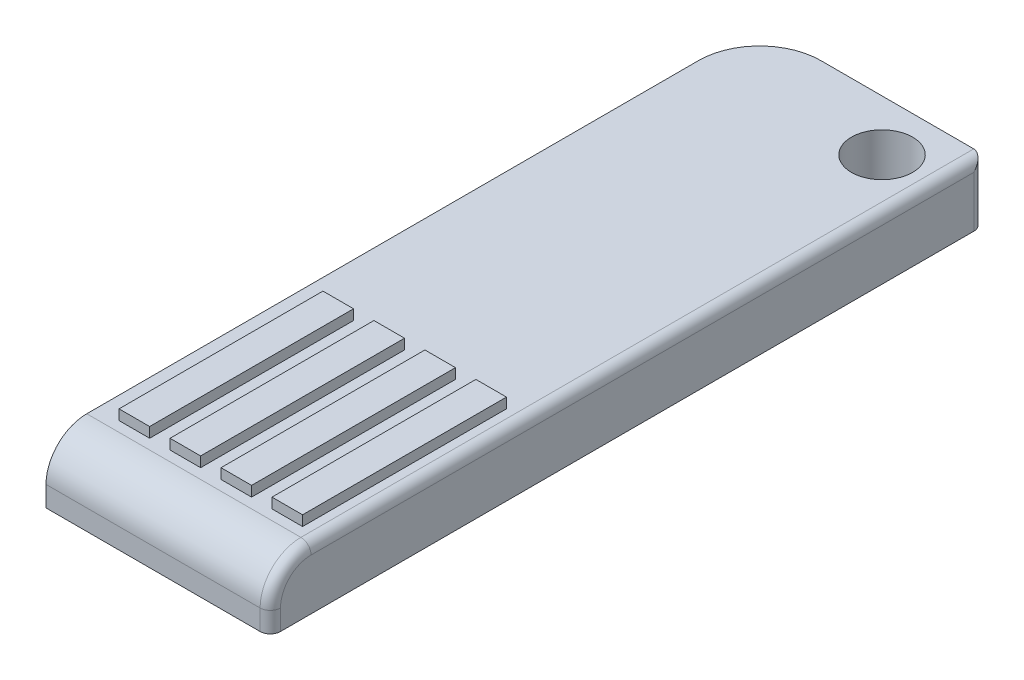
SolidWorks part; units mm, degrees
ref_plane "Front Plane" through (0, 0, 0) normal (0, 0, 1) x (1, 0, 0)
ref_plane "Top Plane" through (0, 0, 0) normal (0, 1, 0) x (1, 0, 0)
ref_plane "Right Plane" through (0, 0, 0) normal (1, 0, 0) x (0, 0, -1)
sketch "Sketch1" plane through (0, 0, 0) normal (0, 1, 0) x (1, 0, 0)
  line L1 (-5.5, 17.5) -> (5.5, 17.5)
  line L2 (-5.5, 17.5) -> (-5.5, -17.5)
  line L3 (-5.5, -17.5) -> (5.5, -17.5)
  line L4 (5.5, 17.5) -> (5.5, -17.5)
  line L5 (-5.5, 17.5) -> (5.5, -17.5) construction
  line L6 (-5.5, -17.5) -> (5.5, 17.5) construction
  point P0 (0, 0)
  dimension "D1" = 11
  dimension "D2" = 35
extrude "Boss-Extrude1" add sketch "Sketch1" along normal blind 3
sketch "Sketch2" plane through (0, 3, 0) normal (0, 1, 0) x (1, 0, 0)
  circle A0 centre (3, 15) radius 1.5
  dimension "D1" = 3
extrude "Cut-Extrude1" cut sketch "Sketch2" against normal blind 3
fillet "Fillet1" radius 3 1 edges at (-5.5, 1.5, -17.5)
sketch "Sketch3" plane through (0, 3, 0) normal (0, 1, 0) x (1, 0, 0)
  line L0 (-1.9175, -5) -> (-1.9175, -15)
  line L1 (-4.4175, -5) -> (-2.9175, -5)
  line L2 (-4.4175, -5) -> (-4.4175, -15)
  line L3 (-4.4175, -15) -> (-2.9175, -15)
  line L4 (-2.9175, -5) -> (-2.9175, -15)
  line L5 (-4.4175, -5) -> (-2.9175, -15) construction
  line L6 (-4.4175, -15) -> (-2.9175, -5) construction
  line L7 (-1.9175, -5) -> (-0.4175, -5)
  line L8 (-0.4175, -5) -> (-0.4175, -15)
  line L9 (-1.9175, -15) -> (-0.4175, -15)
  line L10 (0.5825, -5) -> (0.5825, -15)
  line L11 (0.5825, -5) -> (2.0825, -5)
  line L12 (2.0825, -5) -> (2.0825, -15)
  line L13 (0.5825, -15) -> (2.0825, -15)
  line L14 (3.0825, -5) -> (3.0825, -15)
  line L15 (3.0825, -5) -> (4.5825, -5)
  line L16 (4.5825, -5) -> (4.5825, -15)
  line L17 (3.0825, -15) -> (4.5825, -15)
  line L18 (-5.5, -17.5) -> (5.5, -17.5) construction
  point P0 (0, -34.4499)
  point P5 (-3.6675, -10)
  point P7 (2.5, -34.4499)
  point P12 (5, -34.4499)
  point P17 (7.5, -34.4499)
  dimension "D1" = 1.5
  dimension "D2" = 10
  dimension "D3" = 4
  dimension "D4" = 7.5
extrude "Boss-Extrude2" add sketch "Sketch3" along normal blind 0.5
fillet "Fillet4" radius 2 1 edges at (0, 3, 17.5)
fillet "Fillet5" radius 0.5 4 edges at (5.5, 3, -1) (5.5, 2.4142, 16.9142) (5.5, 1.5, -17.5) (5.5, 0.5, 17.5)
